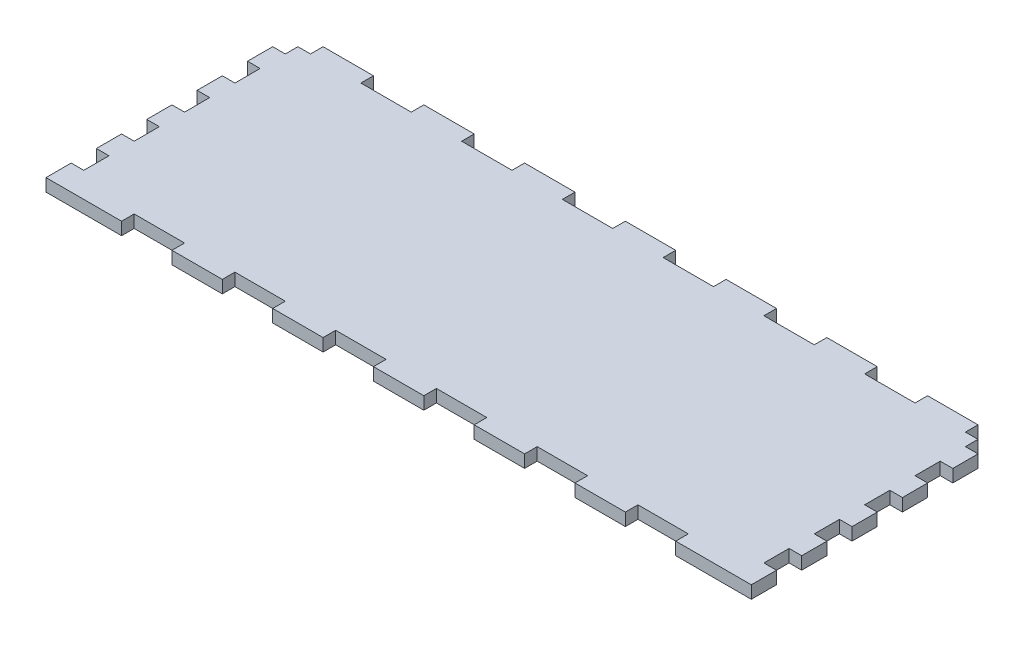
SolidWorks part; units mm, degrees
material "Pin"
ref_plane "Front" through (0, 0, 0) normal (0, 0, 1) x (1, 0, 0)
ref_plane "Top" through (0, 0, 0) normal (0, 1, 0) x (1, 0, 0)
ref_plane "Right" through (0, 0, 0) normal (1, 0, 0) x (0, 0, -1)
sketch "Esquisse1" plane through (0, 0, 0) normal (0, 1, 0) x (1, 0, 0)
  line L1 (-177.8, 63.5) -> (177.8, 63.5)
  line L2 (-177.8, 63.5) -> (-177.8, -63.5)
  line L3 (-177.8, -63.5) -> (177.8, -63.5)
  line L4 (177.8, 63.5) -> (177.8, -63.5)
  line L5 (-177.8, 63.5) -> (177.8, -63.5) construction
  line L6 (-177.8, -63.5) -> (177.8, 63.5) construction
  point P0 (0, 0)
  dimension "D1" = 355.6
  dimension "D2" = 127
extrude "Boss.-Extru.1" add sketch "Esquisse1" along normal blind 6.35
sketch "Esquisse3" plane through (0, 6.35, 0) normal (0, 1, 0) x (1, 0, 0)
  line L0 (177.8, 63.5) -> (-177.8, 63.5) construction
  line L1 (-139.7, 63.5) -> (-114.3, 63.5)
  line L2 (-139.7, 63.5) -> (-139.7, 57.15)
  line L3 (-139.7, 57.15) -> (-114.3, 57.15)
  line L4 (-114.3, 63.5) -> (-114.3, 57.15)
  line L5 (-177.8, 63.5) -> (-177.8, -63.5) construction
  dimension "D1" = 6.35
  dimension "D2" = 25.4
  dimension "D3" = 38.1
extrude "Enlèv. mat.-Extru.2" cut sketch "Esquisse3" against normal blind 6.35
sketch "Esquisse4" plane through (0, 6.35, 0) normal (0, 1, 0) x (1, 0, 0)
  line L0 (-177.8, 63.5) -> (-177.8, -63.5) construction
  line L1 (-177.8, 50.8) -> (-171.45, 50.8)
  line L2 (-177.8, 50.8) -> (-177.8, 63.5)
  line L3 (-177.8, 63.5) -> (-171.45, 63.5)
  line L4 (-171.45, 50.8) -> (-171.45, 63.5)
  line L8 (-139.7, 63.5) -> (-177.8, 63.5) construction
  dimension "D1" = 6.35
  dimension "D2" = 12.7
extrude "Enlèv. mat.-Extru.3" cut sketch "Esquisse4" against normal blind 25.4
pattern_linear "Répétition linéaire1" count 6 spacing 50.8 along (1, 0, 0) count 2 spacing 120.65 along (0, 0, 1) of "Enlèv. mat.-Extru.2"
pattern_linear "Répétition linéaire3" count 5 spacing 25.4 along (0, 0, 1) count 2 spacing 349.25 along (1, 0, 0) of "Enlèv. mat.-Extru.3"
sketch "Esquisse5" plane through (0, 6.35, 0) normal (0, 1, 0) x (1, 0, 0)
  line L0 (-177.8, 50.8) -> (-177.8, 38.1) construction
  line L1 (-177.8, 63.5) -> (-165.1, 63.5)
  line L2 (-177.8, 63.5) -> (-177.8, 57.15)
  line L3 (-177.8, 57.15) -> (-165.1, 57.15)
  line L4 (-165.1, 63.5) -> (-165.1, 57.15)
  line L5 (-139.7, 63.5) -> (-171.45, 63.5) construction
  line L6 (177.8, 38.1) -> (177.8, 50.8) construction
  line L7 (177.8, 63.5) -> (165.1, 63.5)
  line L8 (177.8, 63.5) -> (177.8, 57.15)
  line L9 (177.8, 57.15) -> (165.1, 57.15)
  line L10 (165.1, 63.5) -> (165.1, 57.15)
  line L11 (171.45, 63.5) -> (139.7, 63.5) construction
  line L12 (139.7, 57.15) -> (139.7, 63.5) construction
  dimension "D1" = 6.35
  dimension "D2" = 12.7
  dimension "D3" = 25.4
  dimension "D4" = 6.35
extrude "Enlèv. mat.-Extru.4" cut sketch "Esquisse5" against normal blind 6.35
sketch "Esquisse6" plane through (0, 6.35, 0) normal (0, 1, 0) x (1, 0, 0)
  circle A0 centre (0, 0) radius 44.45
  circle A1 centre (-114.3, 0) radius 44.45
  circle A2 centre (114.3, 0) radius 44.45
  dimension "D1" = 88.9
  dimension "D2" = 114.3
  dimension "D3" = 114.3
